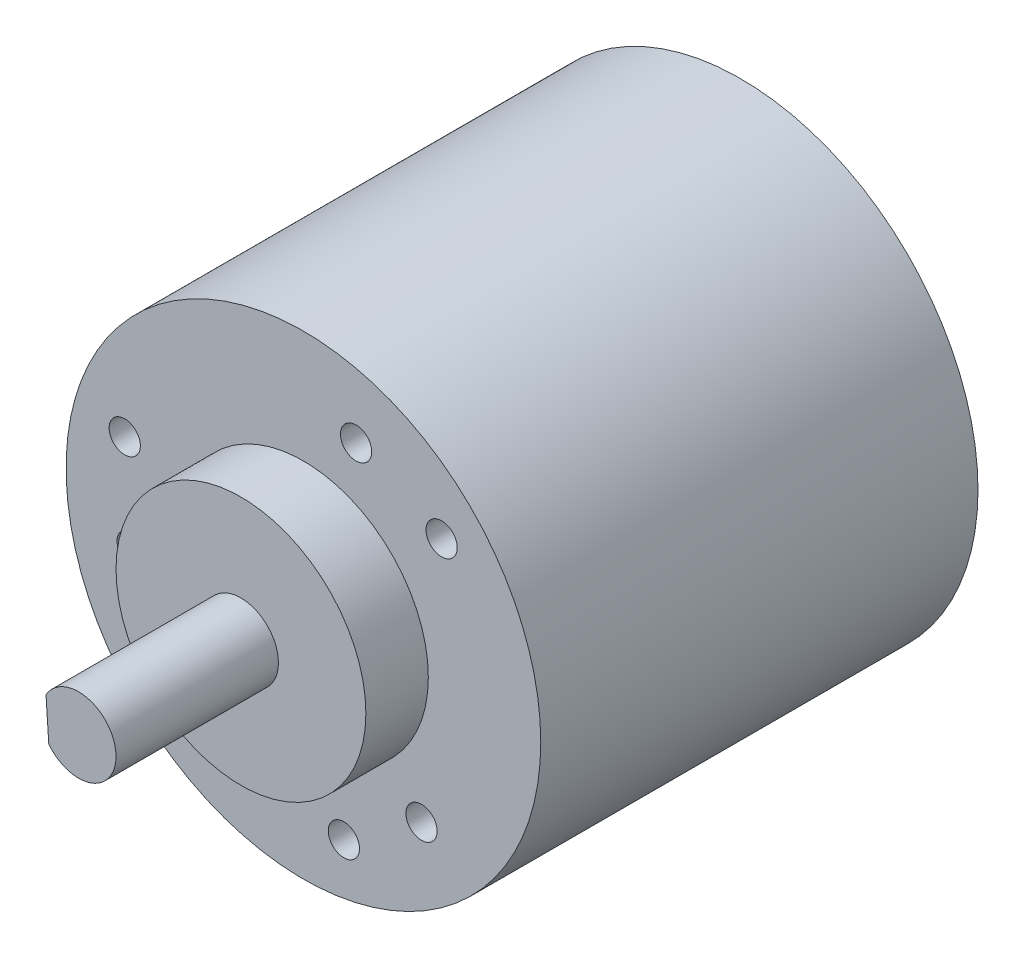
SolidWorks part; units mm, degrees
ref_plane "Plan de face" through (0, 0, 0) normal (0, 0, 1) x (1, 0, 0)
ref_plane "Plan de dessus" through (0, 0, 0) normal (0, 1, 0) x (1, 0, 0)
ref_plane "Plan de droite" through (0, 0, 0) normal (1, 0, 0) x (0, 0, -1)
sketch "Esquisse1" plane through (0, 0, 0) normal (0, 0, 1) x (1, 0, 0)
  circle A0 centre (0, 0) radius 19
  dimension "D1" = 38
extrude "Boss.-Extru.1" add sketch "Esquisse1" along normal blind 35
sketch "Esquisse2" plane through (0, 0, 35) normal (0, 0, 1) x (1, 0, 0)
  circle A0 centre (0, 0) radius 10
extrude "Boss.-Extru.2" add sketch "Esquisse2" along normal blind 5
sketch "Esquisse3" plane through (0, 0, 40) normal (0, 0, 1) x (1, 0, 0)
  circle A0 centre (0, 0) radius 3
  dimension "D1" = 6
extrude "Boss.-Extru.3" add sketch "Esquisse3" along normal blind 13
sketch "Esquisse4" plane through (0, 0, 35) normal (0, 0, 1) x (1, 0, 0)
  line L0 (0, 0) -> (3.2395, -14.646)
  line L1 (0, 0) -> (9.4533, -10.3264)
  line L2 (0, 0) -> (-13.6696, -3.0236)
  line L3 (-14.3036, 4.5175) -> (0, 0)
  line L4 (4.2163, 13.35) -> (0, 0)
  line L5 (11.064, 10.1285) -> (0, 0)
  circle A0 centre (11.064, 10.1285) radius 1.25
  circle A1 centre (-13.6696, -3.0236) radius 1.25
  circle A2 centre (-14.3036, 4.5175) radius 1.25
  circle A3 centre (3.2395, -14.646) radius 1.25
  circle A4 centre (9.4533, -10.3264) radius 1.25
  circle A5 centre (4.2163, 13.35) radius 1.25
  dimension "D1" = 2.5
  dimension "D2" = 2.5
  dimension "D3" = 2.5
  dimension "D4" = 2.5
  dimension "D5" = 2.5
  dimension "D6" = 2.5
  dimension "D7" = 30
  dimension "D8" = 30
  dimension "D12" = 30
  dimension "D14" = 14
  dimension "D9" = 15
  dimension "D10" = 15
  dimension "D11" = 14
  dimension "D13" = 14
  dimension "D15" = 120
  dimension "D16" = 120
extrude "Enlèv. mat.-Extru.1" cut sketch "Esquisse4" against normal blind 8
sketch "Esquisse6" plane through (0, 0, 53) normal (0, 0, 1) x (1, 0, 0)
  line L0 (-2.3824, -1.8232) -> (-2.6062, 1.4859)
  line L1 (-2.6062, 1.4859) -> (-6.1394, 1.2469)
  line L2 (-6.1394, 1.2469) -> (-5.9156, -2.0621)
  line L3 (-5.9156, -2.0621) -> (-2.3824, -1.8232)
  circle A0 centre (0, 0) radius 3 construction
  dimension "D1" = 2.5
extrude "Enlèv. mat.-Extru.2" cut sketch "Esquisse6" against normal blind 13
